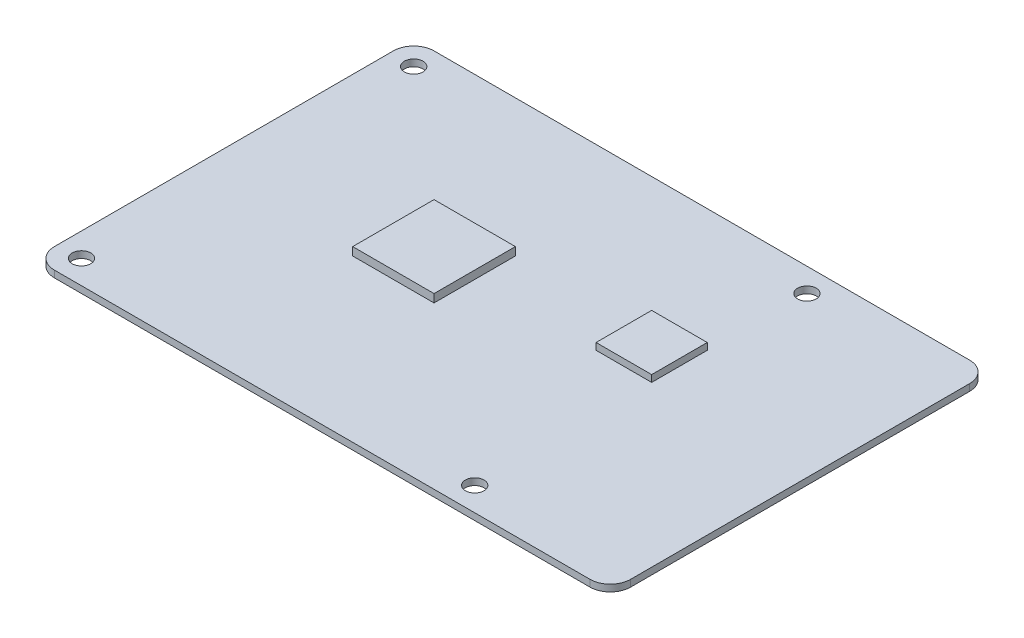
SolidWorks part; units mm, degrees
ref_plane "Спереди" through (0, 0, 0) normal (0, 0, 1) x (1, 0, 0)
ref_plane "Сверху" through (0, 0, 0) normal (0, 1, 0) x (1, 0, 0)
ref_plane "Справа" through (0, 0, 0) normal (1, 0, 0) x (0, 0, -1)
sketch "Эскиз1" plane through (0, 0, 0) normal (0, 1, 0) x (1, 0, 0)
  line L1 (42.5, -28) -> (-42.5, -28)
  line L2 (42.5, -28) -> (42.5, 28)
  line L3 (42.5, 28) -> (-42.5, 28)
  line L4 (-42.5, -28) -> (-42.5, 28)
  line L5 (42.5, -28) -> (-42.5, 28) construction
  line L6 (42.5, 28) -> (-42.5, -28) construction
  point P0 (0, 0)
  dimension "D1" = 56
  dimension "D2" = 85
extrude "Бобышка-Вытянуть1" add sketch "Эскиз1" along normal blind 1
fillet "Скругление1" radius 3 4 edges at (-42.5, 0.5, -28) (42.5, 0.5, -28) (42.5, 0.5, 28) (-42.5, 0.5, 28)
sketch "Эскиз2" plane through (0, 1, 0) normal (0, 1, 0) x (1, 0, 0)
  line L1 (39.5, 28) -> (-39.5, 28) construction
  line L2 (-42.5, 25) -> (-42.5, -25) construction
  line L4 (39.5, 28) -> (-39.5, 28) construction
  line L5 (-42.5, 25) -> (-42.5, -25) construction
  line L6 (-39.5, -28) -> (39.5, -28) construction
  circle A0 centre (19, 24.5) radius 1.375
  circle A1 centre (-39, 24.5) radius 1.375
  circle A2 centre (-39, -24.5) radius 1.375
  circle A3 centre (19, -24.5) radius 1.375
  dimension "D1" = 58
  dimension "D3" = 2.75
  dimension "D6" = 2.75
  dimension "D7" = 3.5
  dimension "D9" = 2.75
  dimension "D11" = 2.75
  dimension "D2" = 3.5
  dimension "D4" = 3.5
  dimension "D5" = 3.5
  dimension "D8" = 3.5
  dimension "D10" = 3.5
  dimension "D12" = 58
  dimension "D13" = 49
extrude "Вырез-Вытянуть1" cut sketch "Эскиз2" against normal through all
sketch "Эскиз3" plane through (0, 1, 0) normal (0, 1, 0) x (1, 0, 0)
  line L0 (-42.5, 25) -> (-42.5, -25) construction
  line L1 (-19.3, 7.8) -> (-7.3, 7.8)
  line L2 (-19.3, 7.8) -> (-19.3, -4.2)
  line L3 (-19.3, -4.2) -> (-7.3, -4.2)
  line L4 (-7.3, 7.8) -> (-7.3, -4.2)
  line L5 (-19.3, 7.8) -> (-7.3, -4.2) construction
  line L6 (-19.3, -4.2) -> (-7.3, 7.8) construction
  line L7 (-39.5, -28) -> (39.5, -28) construction
  point P0 (-13.3, 1.8)
  dimension "D1" = 29.2
  dimension "D2" = 12
  dimension "D3" = 12
  dimension "D4" = 29.8
extrude "Бобышка-Вытянуть2" add sketch "Эскиз3" along normal blind 1.2
sketch "Эскиз4" plane through (0, 1, 0) normal (0, 1, 0) x (1, 0, 0)
  line L0 (42.5, -25) -> (42.5, 25) construction
  line L1 (10.7, 9.9) -> (18.9, 9.9)
  line L2 (10.7, 9.9) -> (10.7, 1.7)
  line L3 (10.7, 1.7) -> (18.9, 1.7)
  line L4 (18.9, 9.9) -> (18.9, 1.7)
  line L5 (10.7, 9.9) -> (18.9, 1.7) construction
  line L6 (10.7, 1.7) -> (18.9, 9.9) construction
  line L7 (39.5, 28) -> (-39.5, 28) construction
  point P0 (14.8, 5.8)
  dimension "D1" = 27.7
  dimension "D2" = 22.2
  dimension "D3" = 8.2
  dimension "D4" = 8.2
extrude "Бобышка-Вытянуть3" add sketch "Эскиз4" along normal blind 1
